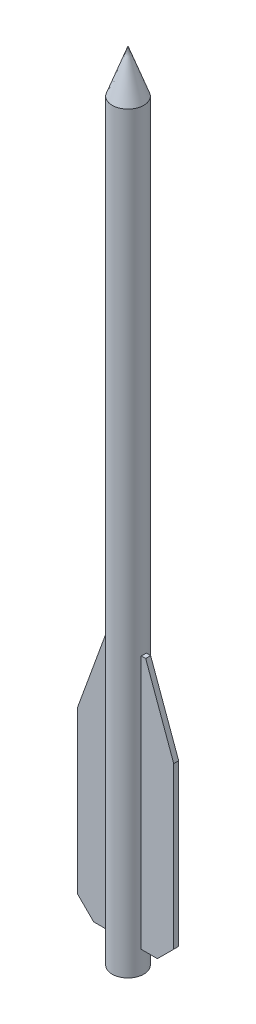
SolidWorks part; units mm, degrees
ref_plane "Front" through (0, 0, 0) normal (0, 0, 1) x (1, 0, 0)
ref_plane "Top" through (0, 0, 0) normal (0, 1, 0) x (1, 0, 0)
ref_plane "Right" through (0, 0, 0) normal (1, 0, 0) x (0, 0, -1)
sketch "Sketch1" plane through (0, 0, 0) normal (0, 1, 0) x (1, 0, 0)
  circle A0 centre (0, 0) radius 3.2
  dimension "D1" = 6.4
extrude "Boss-Extrude1" add sketch "Sketch1" along normal blind 161
ref_plane "Center" through (0, 80.5, 0) normal (0, 1, 0) x (1, 0, 0)
chamfer "Chamfer1" distance 3.2 angle 70 1 edges at (0, 161, 3.2)
sketch "Sketch2" plane through (0, 0, 0) normal (0, 0, 1) x (1, 0, 0)
  line L0 (0, 0) -> (0, 161) construction
  line L1 (0, 4.6) -> (-6.45, 4.6)
  line L2 (-6.45, 4.6) -> (-9.75, 7.9)
  line L3 (-9.75, 7.9) -> (-9.75, 40.4251)
  line L4 (-9.75, 40.4251) -> (-4.0812, 56)
  line L5 (-4.0812, 56) -> (0, 56)
  line L6 (0, 56) -> (0, 4.6)
  point P10 (-5.3035, 4.6)
  point P11 (-6.397, 4.6)
  dimension "D1" = 19.5
  dimension "D2" = 4.6
  dimension "D3" = 45
  dimension "D4" = 3.3
  dimension "D5" = 20
  dimension "D6" = 56
extrude "Fletching" add sketch "Sketch2" along normal mid plane 1
mirror "Fletchings" about plane through (0, 0, 0) normal (1, 0, 0) of "Fletching"
